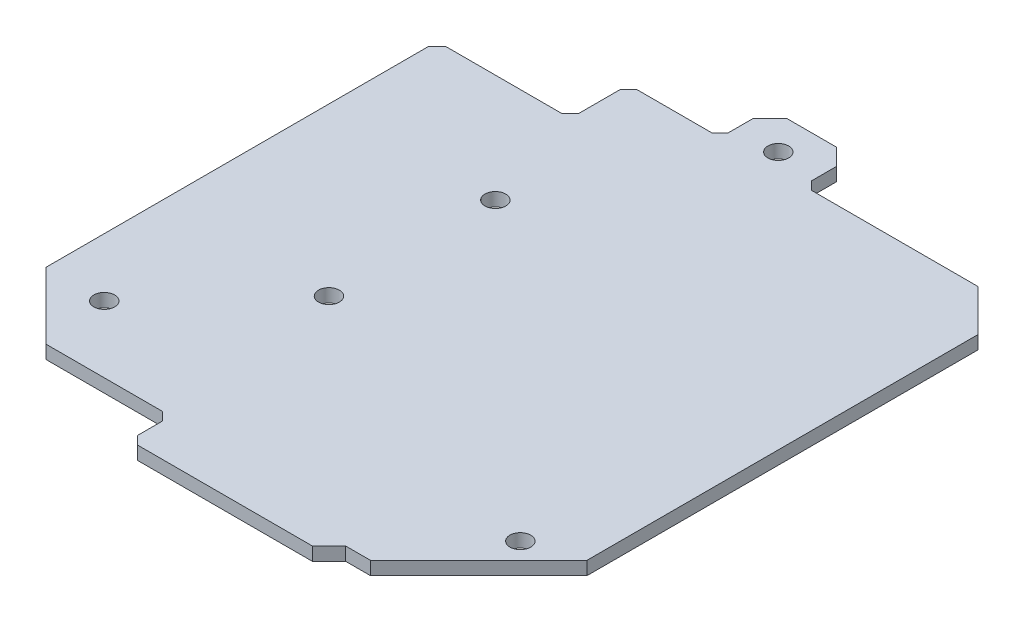
SolidWorks part; units mm, degrees
ref_plane "Спереди" through (0, 0, 0) normal (0, 0, 1) x (1, 0, 0)
ref_plane "Сверху" through (0, 0, 0) normal (0, 1, 0) x (1, 0, 0)
ref_plane "Справа" through (0, 0, 0) normal (1, 0, 0) x (0, 0, -1)
sketch "Эскиз1" plane through (0, 0, 0) normal (0, 1, 0) x (1, 0, 0)
  line L0 (0, -1046.1213) -> (0, 51259.9461) construction
  line L1 (-1046.1213, 0) -> (51259.9461, 0) construction
  line L2 (-32, -24) -> (-32, 22)
  line L3 (31, 25) -> (31, -22)
  line L4 (-3, 36) -> (3, 36)
  line L5 (3, 36) -> (5, 34)
  line L6 (5, 34) -> (5, 31)
  line L7 (5, 31) -> (6, 30)
  line L8 (6, 30) -> (26, 30)
  line L9 (26, 30) -> (31, 25)
  line L10 (-5, 31) -> (-6, 30)
  line L11 (-5, 34) -> (-5, 31)
  line L12 (-3, 36) -> (-5, 34)
  line L13 (-6, 30) -> (-15, 30)
  line L14 (-15, 30) -> (-16, 29)
  line L15 (-16, 29) -> (-16, 24)
  line L16 (-16, 24) -> (-17, 23)
  line L17 (-17, 23) -> (-31, 23)
  line L18 (-31, 23) -> (-32, 22)
  line L19 (-32, -24) -> (-24, -32)
  line L20 (-24, -32) -> (-10, -32)
  line L21 (-10, -32) -> (-9, -33)
  line L22 (-9, -33) -> (-9, -36)
  line L23 (-9, -36) -> (-8, -37)
  line L24 (-8, -37) -> (13, -37)
  line L25 (13, -37) -> (15, -35)
  line L26 (15, -35) -> (18, -35)
  line L27 (18, -35) -> (31, -22)
  circle A0 centre (-25, -24) radius 1.25
  circle A1 centre (25, -24) radius 1.25
  circle A2 centre (0, 32) radius 1.25
  circle A3 centre (-12, -10) radius 1.25
  circle A4 centre (-12, 10) radius 1.25
  point P18 (0, 36)
  dimension "D3" = 2.5
  dimension "D1" = 25
  dimension "D2" = 24
  dimension "D4" = 32
  dimension "D5" = 31
  dimension "D6" = 32
  dimension "D7" = 6
  dimension "D8" = 36
  dimension "D9" = 45
  dimension "D10" = 1
  dimension "D11" = 10
  dimension "D12" = 30
  dimension "D13" = 7
  dimension "D14" = 16
  dimension "D15" = 5
  dimension "D16" = 37
  dimension "D17" = 24
  dimension "D18" = 2
  dimension "D19" = 22
  dimension "D20" = 32
  dimension "D21" = 9
  dimension "D22" = 13
  dimension "D23" = 20
  dimension "D24" = 12
extrude "Бобышка-Вытянуть1" add sketch "Эскиз1" along normal blind 1.6
